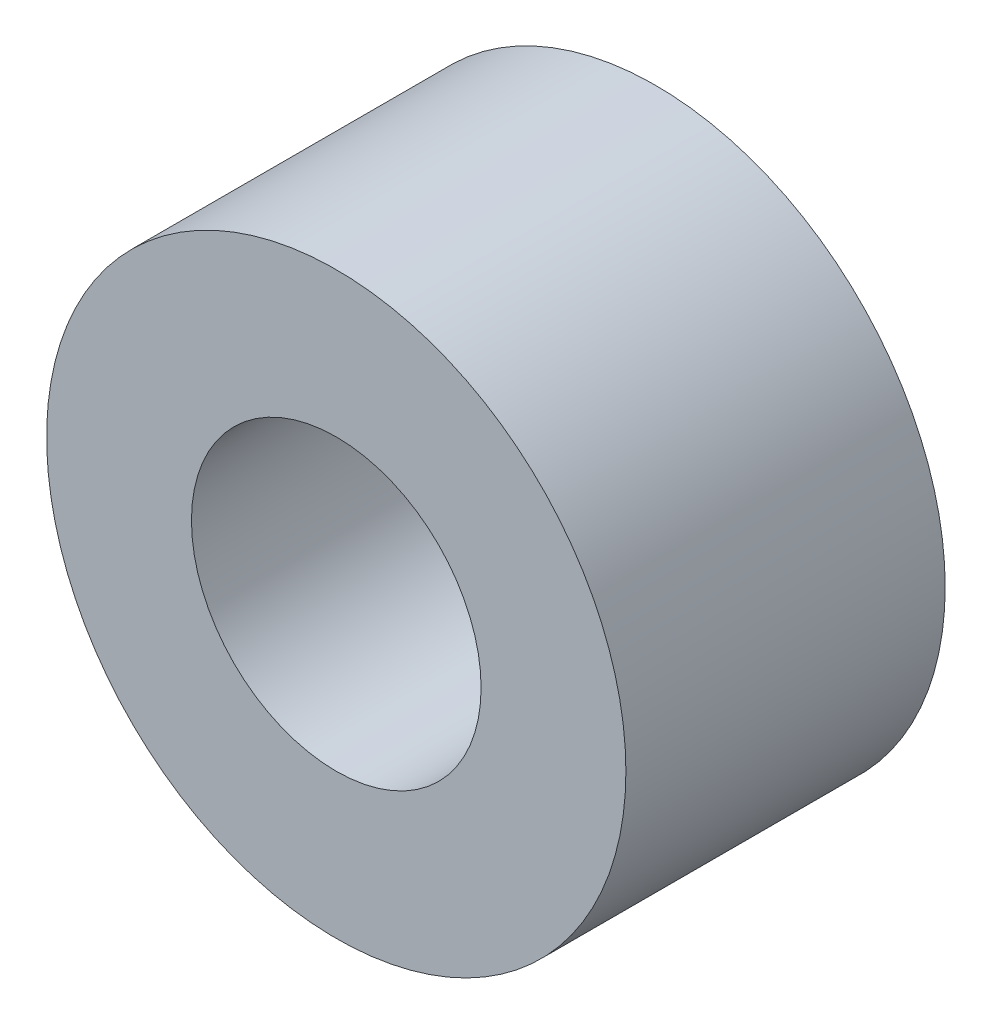
SolidWorks part; units mm, degrees
ref_plane "Front Plane" through (0, 0, 0) normal (0, 0, 1) x (1, 0, 0)
ref_plane "Top Plane" through (0, 0, 0) normal (0, 1, 0) x (1, 0, 0)
ref_plane "Right Plane" through (0, 0, 0) normal (1, 0, 0) x (0, 0, -1)
sketch "Sketch1" plane through (0, 0, 0) normal (0, 0, 1) x (1, 0, 0)
  circle A0 centre (0, 0) radius 6.35
  circle A1 centre (0, 0) radius 3.175
  dimension "D1" = 12.7
  dimension "D2" = 6.35
extrude "Boss-Extrude1" add sketch "Sketch1" along normal blind 7
sketch "Sketch2" plane through (0, 0, 0) normal (1, 0, 0) x (0, 0, -1)
  circle A0 centre (-61.1906, 0) radius 59.5
  circle A1 centre (-61.1906, 0) radius 54.5
  dimension "D1" = 119
  dimension "D2" = 109
